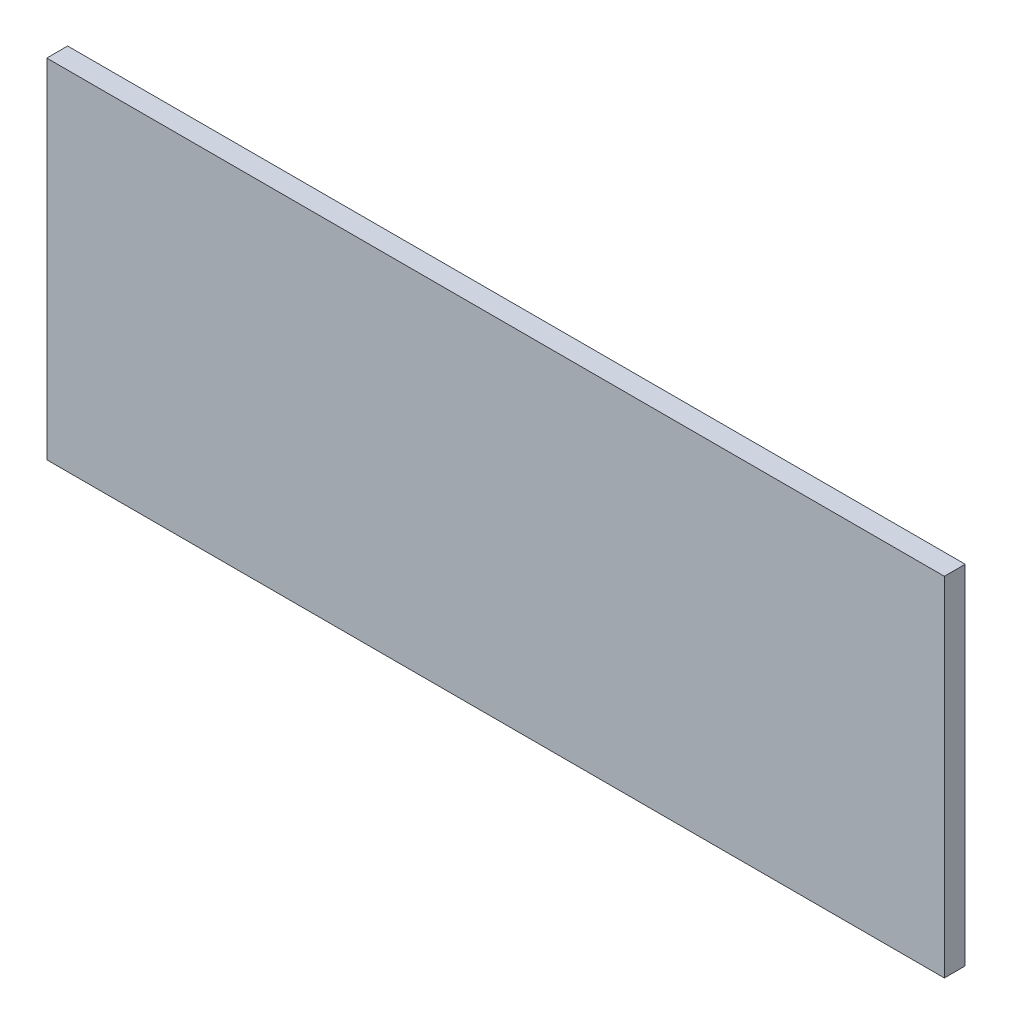
SolidWorks part; units mm, degrees
ref_plane "Plano frontal" through (0, 0, 0) normal (0, 0, 1) x (1, 0, 0)
ref_plane "Plano superior" through (0, 0, 0) normal (0, 1, 0) x (1, 0, 0)
ref_plane "Plano direito" through (0, 0, 0) normal (1, 0, 0) x (0, 0, -1)
sketch "Esboço1" plane through (0, 0, 0) normal (0, 0, 1) x (1, 0, 0)
  line L0 (0, 0) -> (0, 100)
  line L1 (0, 100) -> (-258, 100)
  line L2 (-258, 100) -> (-258, 0)
  line L3 (-258, 0) -> (0, 0)
  dimension "D1" = 100
  dimension "D2" = 258
extrude "Ressalto-extrusão1" add sketch "Esboço1" along normal blind 6
